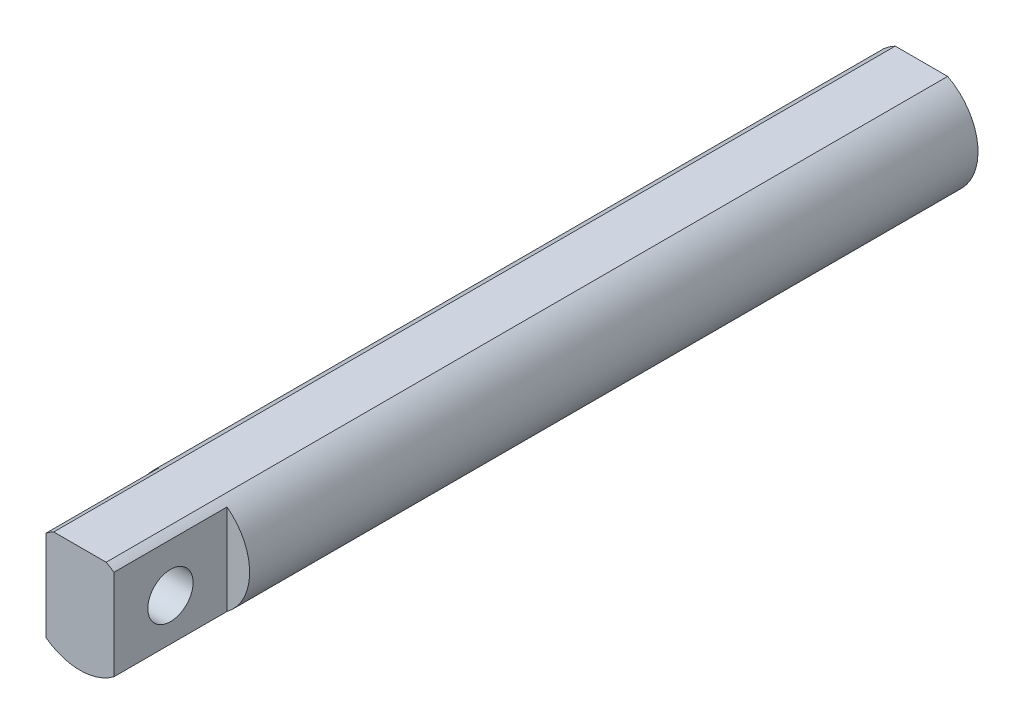
SolidWorks part; units mm, degrees
ref_plane "Alzado" through (0, 0, 0) normal (0, 0, 1) x (1, 0, 0)
ref_plane "Planta" through (0, 0, 0) normal (0, 1, 0) x (1, 0, 0)
ref_plane "Vista lateral" through (0, 0, 0) normal (1, 0, 0) x (0, 0, -1)
sketch "Croquis1" plane through (0, 0, 0) normal (0, 0, 1) x (1, 0, 0)
  circle A0 centre (0, 0) radius 10
  dimension "D1" = 20
extrude "Saliente-Extruir1" add sketch "Croquis1" along normal blind 148.75
sketch "Croquis2" plane through (0, 0, 148.75) normal (0, 0, 1) x (1, 0, 0)
  line L0 (0, 0) -> (0, 15.2644) construction
  line L2 (-6, 11.7942) -> (-14.3005, 11.7942)
  line L3 (-6, 11.7942) -> (-6, -13.2948)
  line L4 (-6, -13.2948) -> (-14.3005, -13.2948)
  line L5 (-14.3005, 11.7942) -> (-14.3005, -13.2948)
  line L6 (6, 12.1693) -> (14.2536, 12.1693)
  line L7 (6, 12.1693) -> (6, -14.3734)
  line L8 (6, -14.3734) -> (14.2536, -14.3734)
  line L9 (14.2536, 12.1693) -> (14.2536, -14.3734)
  dimension "D1" = 6
  dimension "D2" = 6
extrude "Cortar-Extruir1" cut sketch "Croquis2" against normal blind 20
sketch "Croquis3" plane through (0, 0, 148.75) normal (0, 0, 1) x (1, 0, 0)
  line L1 (-5.477, 10.9613) -> (5.1518, 10.9613)
  line L2 (-5.477, 10.9613) -> (-5.477, 8.8614)
  line L3 (-5.477, 8.8614) -> (5.1518, 8.8614)
  line L4 (5.1518, 10.9613) -> (5.1518, 8.8614)
extrude "Cortar-Extruir2" cut sketch "Croquis3" against normal blind 220
sketch "Croquis4" plane through (-6, 0, 0) normal (-1, 0, 0) x (0, 0, 1)
  line L0 (186.6313, 8.8614) -> (186.6313, -9.9666) construction
  line L1 (148.75, 8.8614) -> (0, 8.8614) construction
  line L2 (186.6313, -0.5526) -> (214.4913, -0.5526) construction
  line L3 (148.75, -8) -> (148.75, 8) construction
  circle A0 centre (138.75, -0.5526) radius 4
  dimension "D1" = 8
  dimension "D2" = 10
extrude "Cortar-Extruir3" cut sketch "Croquis4" against normal through all
